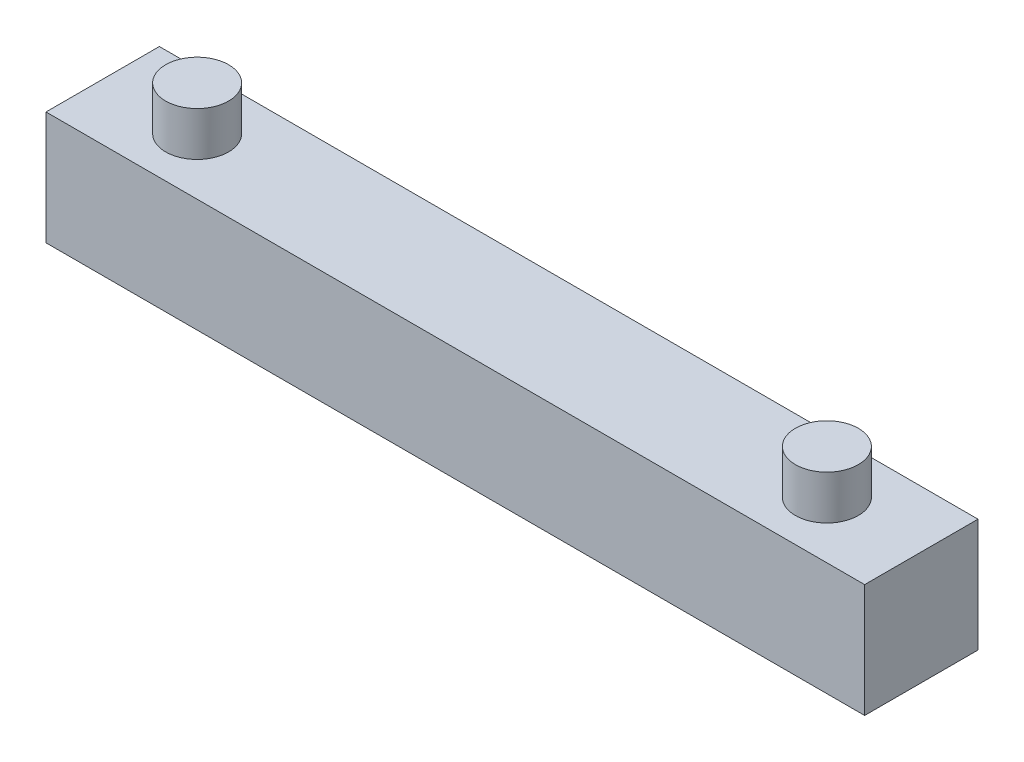
SolidWorks part; units mm, degrees
ref_plane "前基準面" through (0, 0, 0) normal (0, 0, 1) x (1, 0, 0)
ref_plane "上基準面" through (0, 0, 0) normal (0, 1, 0) x (1, 0, 0)
ref_plane "右基準面" through (0, 0, 0) normal (1, 0, 0) x (0, 0, -1)
sketch "草圖1" plane through (0, 0, 0) normal (0, 1, 0) x (1, 0, 0)
  line L1 (-32.5, -4.5) -> (32.5, -4.5)
  line L2 (-32.5, -4.5) -> (-32.5, 4.5)
  line L3 (-32.5, 4.5) -> (32.5, 4.5)
  line L4 (32.5, -4.5) -> (32.5, 4.5)
  line L5 (-32.5, -4.5) -> (32.5, 4.5) construction
  line L6 (-32.5, 4.5) -> (32.5, -4.5) construction
  point P0 (0, 0)
  dimension "D1" = 65
  dimension "D2" = 9
extrude "填料-伸長1" add sketch "草圖1" along normal blind 9
sketch "草圖2" plane through (0, 9, 0) normal (0, 1, 0) x (1, 0, 0)
  line L0 (-25, 0) -> (25, 0)
  line L1 (-32.5, -4.5) -> (32.5, -4.5) construction
  line L2 (32.5, -4.5) -> (32.5, 4.5) construction
  circle A0 centre (-25, 0) radius 2.5
  circle A1 centre (25, 0) radius 2.5
  dimension "D4" = 5
  dimension "D5" = 5
  dimension "D1" = 4.5
  dimension "D2" = 50
  dimension "D3" = 7.5
extrude "填料-伸長2" add sketch "草圖2" along normal blind 3.5
